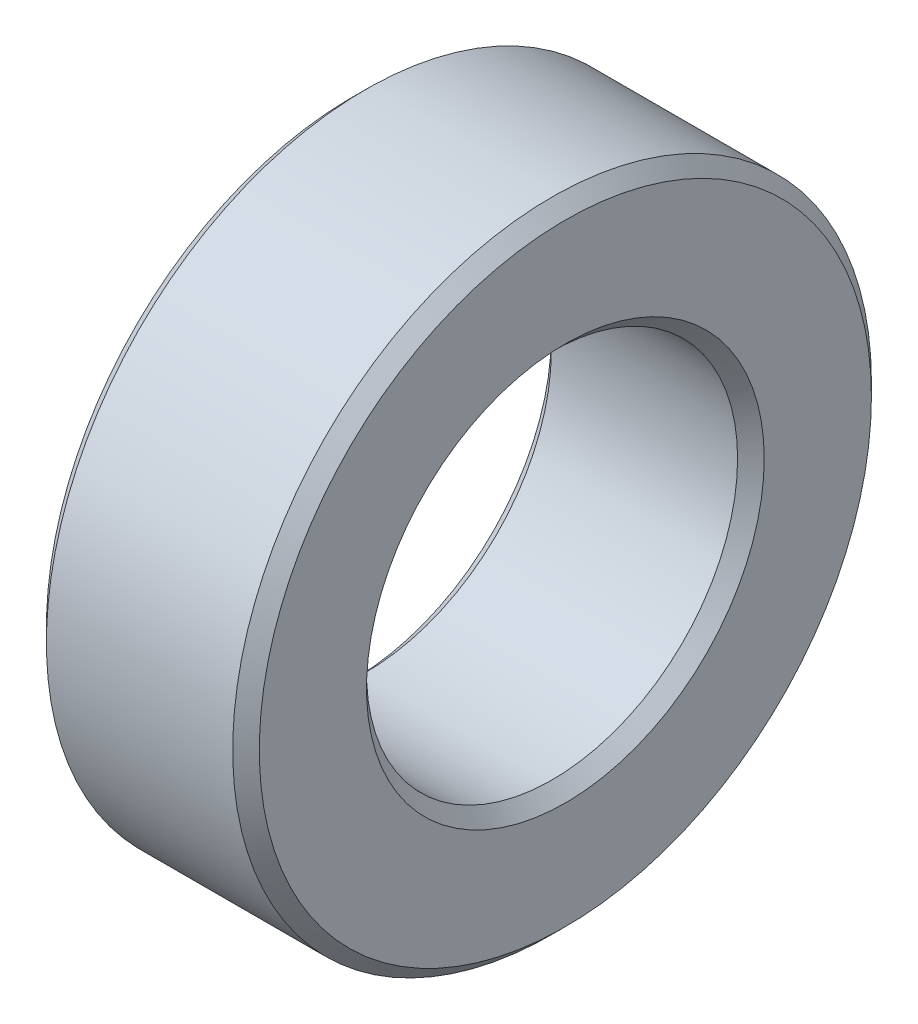
SolidWorks part; units mm, degrees
material "Pure Gold"
ref_plane "Front Plane" through (0, 0, 0) normal (0, 0, 1) x (1, 0, 0)
ref_plane "Top Plane" through (0, 0, 0) normal (0, 1, 0) x (1, 0, 0)
ref_plane "Right Plane" through (0, 0, 0) normal (1, 0, 0) x (0, 0, -1)
sketch "Sketch1" plane through (0, 0, 0) normal (1, 0, 0) x (0, 0, -1)
  circle A0 centre (0, 0) radius 6
  circle A1 centre (0, 0) radius 3.486
  dimension "D1" = 12
  dimension "D2" = 6.972
extrude "Boss-Extrude1" add sketch "Sketch1" along normal blind 4
chamfer "Chamfer1" distance 0.25 angle 45 4 edges at (4, 0, -6) (0, 0, -6) (0, 0, -3.486) (4, 0, -3.486)
